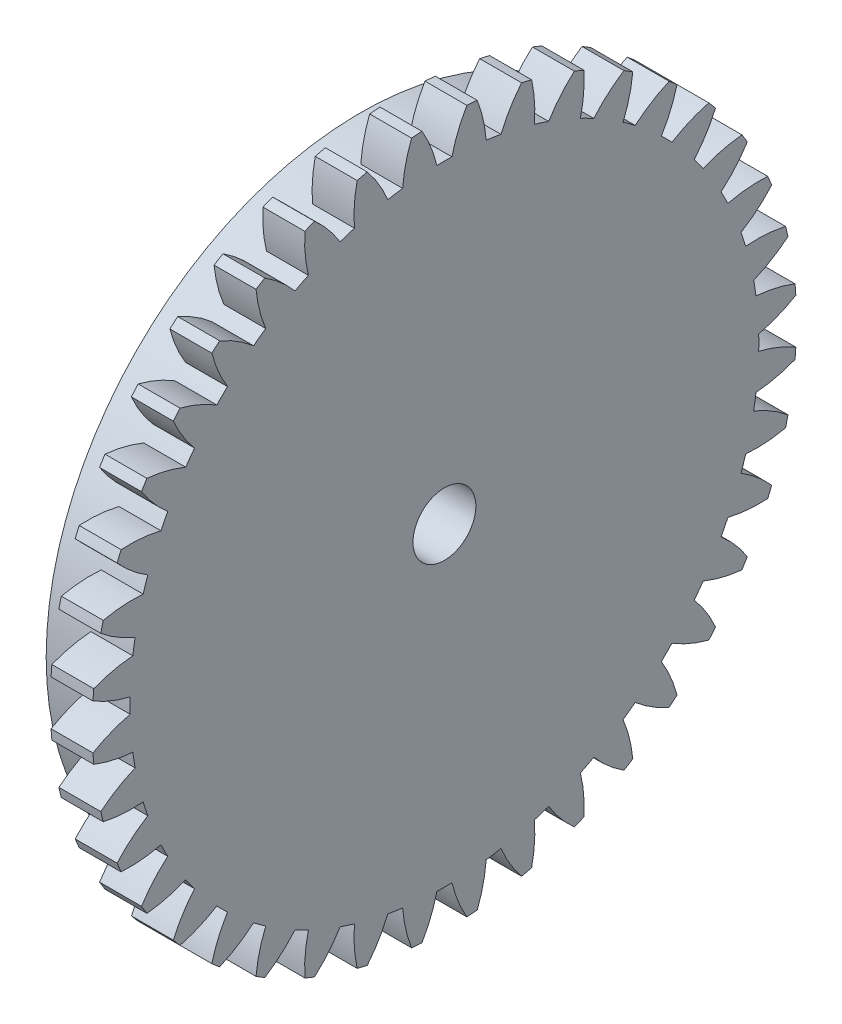
SolidWorks part; units mm, degrees
ref_plane "Plane1" through (0, 0, 0) normal (0, 0, 1) x (1, 0, 0)
ref_plane "Plane2" through (0, 0, 0) normal (0, 1, 0) x (1, 0, 0)
ref_plane "Plane3" through (0, 0, 0) normal (1, 0, 0) x (0, 0, -1)
sketch "HoldingSke" plane through (0, 0, 0) normal (0, 1, 0) x (1, 0, 0)
  line L0 (0, 0) -> (0.9576, -0.8035)
  line L1 (-15, 0) -> (100, 0) construction
  line L2 (0, 0) -> (-2.1039, 2.3779)
  line L3 (0, 0) -> (-11.863, 4.5341)
  line L4 (0, 0) -> (6.6156, 5.5511)
  line L5 (0, 0) -> (-3.7478, -1.3978)
  line L6 (0, 0) -> (-1.6579, -1.1186)
  line L7 (-2.1039, 2.3779) -> (-1.2429, 6.2842)
  line L8 (-76.2, 54.61) -> (-75.7, 54.61)
  line L9 (-71.009, 38.7566) -> (-53.1078, 45.2721)
  line L10 (-76.2, 71.12) -> (104.1128, 71.12)
  line L11 (0, 0) -> (-2, 0)
  line L12 (-76.2, 101.6) -> (-76.17, 101.6)
  line L13 (24.9733, 27.94) -> (52.9518, 28.4284)
  line L14 (24.9733, 27.94) -> (24.9743, 27.94)
  line L15 (24.9733, 27.94) -> (100.4006, 29.5858)
  line L16 (-63.627, -0.8) -> (-12.827, -0.8)
  circle A0 centre (0, 0) radius 1.5
  circle A1 centre (0, 0) radius 14.999
  circle A2 centre (0, 0) radius 20
  circle A3 centre (0, 0) radius 1.5
  dimension "MHD" = 29.998
  dimension "Hub_dia" = 40
  dimension "Bore" = 3
  dimension "MBD" = 3
  dimension "Num_teeth" = 40
  dimension "Pitch" = 1.25
  dimension "Overall_len" = 4
  dimension "Show_teeth" = 40
  dimension "Thickness" = 2
  dimension "OAL" = 4.0001
  dimension "T_dim" = 0.5
  dimension "Ap" = 20
  dimension "H" = 19.05
  dimension "Pitch_radius" = 180.3128
  dimension "Width" = 2
  dimension "Backlash" = 0.03
  dimension "Addendum_fac" = 1
  dimension "Dedendum_fac" = 1.25
  dimension "Clearance_fac" = 0.25
  dimension "Dedendum_add" = 0.001
  dimension "Module" = 0.8
sketch "BasProSke" plane through (0, 0, 0) normal (0, 1, 0) x (1, 0, 0)
  line L0 (-10, 0) -> (60, 0) construction
  line L1 (0, 0) -> (0, 16.8)
  line L2 (0, 0) -> (2, 0)
  line L3 (2, 0) -> (2, 16.8)
  line L4 (2, 16.8) -> (0, 16.8)
  dimension "Thickness" = 2
  dimension "Diameter" = 33.6
revolve "Base-Revolve" add sketch "BasProSke" angle 360 about L0
sketch "TooCutSke" plane through (0, 0, 0) normal (1, 0, 0) x (0, 0, -1)
  line L1 (0, 0) -> (0, 107) construction
  line L2 (0, 0) -> (-0.6807, 15.9855) construction
  line L3 (0, 0) -> (-2.5091, 31.8807) construction
  line L4 (-0.6807, 15.9855) -> (-1.2545, 15.9404) construction
  arc A0 (0.3582, 14.9947) -> (-0.3582, 14.9947) centre (0, 0) ccw
  arc A1 (1.086, 16.7903) -> (-1.086, 16.7903) centre (0, 0) ccw
  circle A2 centre (0, 0) radius 16 construction
  circle A3 centre (0, 0) radius 15.0351 construction
  arc A4 (-0.3582, 14.9947) -> (-1.086, 16.7903) centre (-6.5851, 13.5163) ccw
  arc A5 (1.086, 16.7903) -> (0.3582, 14.9947) centre (6.5851, 13.5163) ccw
  dimension "Root_dia" = 29.998
  dimension "Overcut_dia" = 33.6508
  dimension "Pitch_dia" = 32
  dimension "Base_dia" = 30.0702
  dimension "Flank_rad" = 6.4
  dimension "Half_ang" = 4.5
  dimension "Half_CT" = 0.5757
extrude "ToothCut" cut sketch "TooCutSke" along normal through all
fillet "Breaks" [suppressed] radius 0.016
fillet "RootFillets" [suppressed] radius 0.201
pattern_circular "TeethCuts" count 40 every 9 about axis through (-10, 0, 0) along (1, 0, 0) of "ToothCut", "RootFillets", "Breaks"
sketch "HubNeaOneSke" plane through (0, 0, 0) normal (-1, 0, 0) x (0, 0, 1)
  circle A0 centre (0, 0) radius 14.999
  dimension "Diameter" = 29.998
extrude "HubNearOne" add sketch "HubNeaOneSke" along normal blind 2.0001
sketch "HubNeaBotSke" plane through (0, 0, 0) normal (-1, 0, 0) x (0, 0, 1)
  circle A0 centre (0, 0) radius 14.999
  dimension "Diameter" = 29.998
extrude "HubNearBoth" [suppressed] add sketch "HubNeaBotSke" along normal blind 1
ref_plane "FarPln" through (2, 0, 0) normal (1, 0, 0) x (0, 0, -1)
sketch "HubFarSke" plane through (2, 0, 0) normal (1, 0, 0) x (0, 0, -1)
  circle A0 centre (0, 0) radius 14.999
  dimension "Diameter" = 29.998
extrude "HubFar" [suppressed] add sketch "HubFarSke" along normal blind 1
sketch "BorSke" plane through (0, 0, 0) normal (1, 0, 0) x (0, 0, -1)
  circle A0 centre (0, 0) radius 1.5
  dimension "Diameter" = 3
extrude "Bore" cut sketch "BorSke" along normal mid plane 8.0001
sketch "KeySke" plane through (0, 0, 0) normal (1, 0, 0) x (0, 0, -1)
  line L0 (-0.6, 0) -> (-0.6, 2)
  line L1 (-0.6, 2) -> (0.6, 2)
  line L2 (0.6, 2) -> (0.6, 0)
  line L3 (0, 0) -> (0, 34) construction
  line L4 (-0.6, 0) -> (0.6, 0)
  dimension "Offset" = 2
  dimension "Width" = 1.2
extrude "Keyway" [suppressed] cut sketch "KeySke" along normal mid plane 8.0001
pattern_circular "Keyway2" [suppressed] count 2 every 90 about axis through (-10, 0, 0) along (1, 0, 0)
equation "' \"Module@HoldingSke\" = 6.35"
equation "' \"Num_teeth@HoldingSke\" = 12"
equation "' \"Ap@HoldingSke\" =  20"
equation "' \"Ap@HoldingSke\" = 20"
equation "' \"Width@HoldingSke\" = 0.5 * 25.4"
equation "' \"Hub_dia@HoldingSke\"= 1 * 25.4"
equation "' \"Hub_dia@HoldingSke\" = 1 * 25.4"
equation "' \"Overall_len@HoldingSke\" = 1.0 * 25.4"
equation "' \"Bore@HoldingSke\" = 0.75 * 25.4"
equation "' \"T_dim@HoldingSke\" = 0.1 * 25.4"
equation "' \"Width@KeySke\" = 0.25 * 25.4"
equation "' \"Show_teeth@HoldingSke\" = 13"
equation "' \"Backlash@HoldingSke\" = 0.009 * 25.4"
equation "' \"Addendum_fac@HoldingSke\" = 1.0"
equation "' \"Dedendum_fac@HoldingSke\" = 1.25"
equation "' \"Dedendum_add@HoldingSke\" = 0.00005 * 25.4"
equation "' \"Clearance_fac@HoldingSke\" = 0.25"
equation "\"Pitch@HoldingSke\" = 1 / \"Module@HoldingSke\""
equation "\"Overcut_dia@TooCutSke\" = (\"Num_teeth@HoldingSke\" + 2 * \"Addendum_fac@HoldingSke\") / \"Pitch@HoldingSke\" + 0.002 * 25.4"
equation "\"Pitch_dia@TooCutSke\" = \"Num_teeth@HoldingSke\" / \"Pitch@HoldingSke\""
equation "\"Base_dia@TooCutSke\" = \"Num_teeth@HoldingSke\" / \"Pitch@HoldingSke\" * cos((\"Ap@HoldingSke\"  * 3.14159265 / 180))"
equation "\"Root_dia@TooCutSke\" = (\"Num_teeth@HoldingSke\" + 2) / \"Pitch@HoldingSke\" - 2 * (\"Addendum_fac@HoldingSke\" + \"Dedendum_fac@HoldingSke\") / \"Pitch@HoldingSke\" - \"Dedendum_add@HoldingSke\" * 2"
equation "\"Half_ang@TooCutSke\" = 180 / \"Num_teeth@HoldingSke\""
equation "\"Half_CT@TooCutSke\" = \"Num_teeth@HoldingSke\" / \"Pitch@HoldingSke\" * sin((3.14159265 / 2 / \"Num_teeth@HoldingSke\")) / 2 - 7 * \"Backlash@HoldingSke\" / 4"
equation "\"Flank_rad@TooCutSke\" = \"Num_teeth@HoldingSke\" / \"Pitch@HoldingSke\" / 5"
equation "\"Radius@RootFillets\" = \"Clearance_fac@HoldingSke\" / \"Pitch@HoldingSke\" + \"Dedendum_add@HoldingSke\""
equation "\"Break_rad@Breaks\" = 0.02 / \"Pitch@HoldingSke\""
equation "\"Thickness@HoldingSke\" = \"Width@HoldingSke\""
equation "\"OAL@HoldingSke\" = \"Thickness@HoldingSke\""
equation "\"MHD@HoldingSke\" = (\"Num_teeth@HoldingSke\" + 2) / \"Pitch@HoldingSke\" - 2 * (\"Addendum_fac@HoldingSke\" + \"Dedendum_fac@HoldingSke\")  / \"Pitch@HoldingSke\" - \"Dedendum_add@HoldingSke\" * 2"
equation "\"MBD@HoldingSke\" = (\"Num_teeth@HoldingSke\" + 2) / \"Pitch@HoldingSke\" - 2 * (\"Addendum_fac@HoldingSke\" + \"Dedendum_fac@HoldingSke\")  / \"Pitch@HoldingSke\" - \"Dedendum_add@HoldingSke\" * 2 - 0.002 * 25.4"
equation "\"MHD@HoldingSke\" = ((sgn( \"MHD@HoldingSke\" - \"Hub_dia@HoldingSke\" )-1)*( \"MHD@HoldingSke\" - \"Hub_dia@HoldingSke\" ))/-2+ \"Hub_dia@HoldingSke\""
equation "\"MBD@HoldingSke\" = ((sgn( \"MBD@HoldingSke\" - \"Bore@HoldingSke\" )-1)*( \"MBD@HoldingSke\" - \"Bore@HoldingSke\" ))/-2+ \"Bore@HoldingSke\""
equation "\"OAL@HoldingSke\" = ((sgn( \"OAL@HoldingSke\" - \"Overall_len@HoldingSke\" )+1)*( \"OAL@HoldingSke\" - \"Overall_len@HoldingSke\" ))/2 + \"Overall_len@HoldingSke\" + 0.000002 * 25.4"
equation "\"Num_teeth@TeethCuts\" = int( \"Show_teeth@HoldingSke\" ) + 1"
equation "\"Num_teeth@TeethCuts\" = ((sgn( \"Num_teeth@TeethCuts\" - \"Num_teeth@HoldingSke\" )-1)*( \"Num_teeth@TeethCuts\" - \"Num_teeth@HoldingSke\" ))/-2+ \"Num_teeth@HoldingSke\""
equation "\"Num_teeth@TeethCuts\" = ((sgn( \"Num_teeth@TeethCuts\" - 2.0)+1)*( \"Num_teeth@TeethCuts\" - 2.0))/2 +2.0"
equation "\"Angle@TeethCuts\" = 360.0 / \"Num_teeth@HoldingSke\""
equation "\"Diameter@BasProSke\" = (\"Num_teeth@HoldingSke\" + 2 * \"Addendum_fac@HoldingSke\") / \"Pitch@HoldingSke\""
equation "\"Thickness@BasProSke\"  = \"Thickness@HoldingSke\""
equation "' \"Fillet_rad@BasProSke\" =  \"Thickness@HoldingSke\" * 0.05"
equation "' \"Fillet_rad@BasProSke\" = \"Thickness@HoldingSke\" * 0.05"
equation "\"MHD@HoldingSke\" = ((sgn( \"MHD@HoldingSke\" - \"Root_dia@TooCutSke\" )-1)*( \"MHD@HoldingSke\" - \"Root_dia@TooCutSke\" ))/-2+ \"Root_dia@TooCutSke\""
equation "\"Diameter@HubNeaOneSke\" = \"MHD@HoldingSke\""
equation "\"Length@HubNearOne\" = \"OAL@HoldingSke\" - \"Thickness@BasProSke\""
equation "\"Diameter@HubNeaBotSke\" = \"MHD@HoldingSke\""
equation "\"Length@HubNearBoth\" = ( \"OAL@HoldingSke\" - \"Thickness@BasProSke\" ) / 2.0"
equation "\"Thickness@FarPln\" = \"Thickness@BasProSke\""
equation "\"Diameter@HubFarSke\" = \"MHD@HoldingSke\""
equation "\"Length@HubFar\" = ( \"OAL@HoldingSke\" - \"Thickness@BasProSke\" ) / 2.0"
equation "\"Diameter@BorSke\" = \"MBD@HoldingSke\""
equation "\"D1@Bore\" = \"OAL@HoldingSke\" * 2.0"
equation "\"D1@Keyway\" = \"OAL@HoldingSke\" * 2.0"
equation "\"Offset@KeySke\" = \"T_dim@HoldingSke\" + \"MBD@HoldingSke\" / 2.0"
